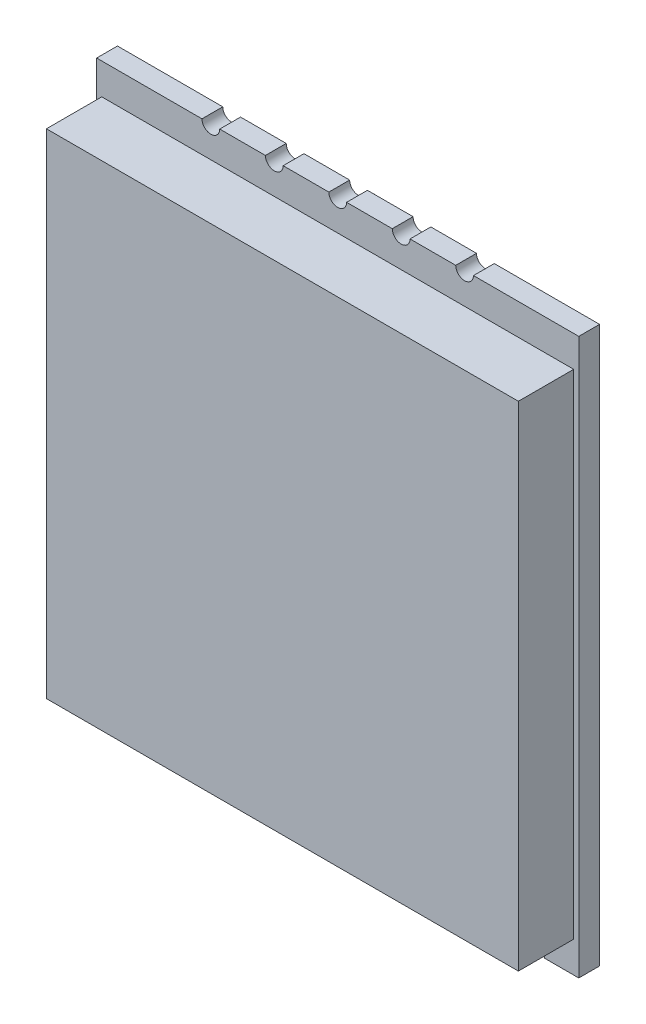
SolidWorks part; units mm, degrees
ref_plane "Front Plane" through (0, 0, 0) normal (0, 0, 1) x (1, 0, 0)
ref_plane "Top Plane" through (0, 0, 0) normal (0, 1, 0) x (1, 0, 0)
ref_plane "Right Plane" through (0, 0, 0) normal (1, 0, 0) x (0, 0, -1)
sketch "Sketch1" plane through (0, 0, 0) normal (0, 0, 1) x (1, 0, 0)
  line L1 (0, 0) -> (19, 0)
  line L2 (0, 0) -> (0, 21.9)
  line L3 (0, 21.9) -> (19, 21.9)
  line L4 (19, 0) -> (19, 21.9)
  dimension "D1" = 19
  dimension "D2" = 21.9
extrude "Boss-Extrude1" add sketch "Sketch1" along normal blind 0.82
sketch "Sketch2" plane through (0, 0, 0.82) normal (0, 0, 1) x (1, 0, 0)
  line L1 (0.2, 1.225) -> (18.8, 1.225)
  line L2 (0.2, 1.225) -> (0.2, 20.675)
  line L3 (0.2, 20.675) -> (18.8, 20.675)
  line L4 (18.8, 1.225) -> (18.8, 20.675)
  line L5 (0, 10.95) -> (0.2, 10.95) construction
  line L6 (0, 21.9) -> (0, 0) construction
  line L7 (18.8, 10.95) -> (19, 10.95) construction
  line L8 (19, 0) -> (19, 21.9) construction
  dimension "D1" = 18.6
  dimension "D2" = 19.45
extrude "Boss-Extrude2" add sketch "Sketch2" along normal blind 2.18
sketch "Sketch3" plane through (0, 0, 0.82) normal (0, 0, 1) x (1, 0, 0)
  line L0 (19, 21.9) -> (0, 21.9) construction
  line L1 (0, 0) -> (19, 0) construction
  line L2 (19, 0) -> (19, 21.9) construction
  circle A0 centre (4.5, 21.9) radius 0.35
  circle A1 centre (7, 21.9) radius 0.35
  circle A2 centre (9.5, 21.9) radius 0.35
  circle A3 centre (12, 21.9) radius 0.35
  circle A4 centre (14.5, 21.9) radius 0.35
  circle A5 centre (4.3, 0) radius 0.35
  circle A6 centre (6.9, 0) radius 0.35
  circle A7 centre (9.5, 0) radius 0.35
  circle A8 centre (12.1, 0) radius 0.35
  circle A9 centre (14.7, 0) radius 0.35
  circle A10 centre (17.3, 0) radius 0.35
  dimension "D1" = 0.7
  dimension "D2" = 4.5
  dimension "D3" = 2.5
  dimension "D4" = 2.5
  dimension "D5" = 2.5
  dimension "D6" = 2.5
  dimension "D7" = 4.5
  dimension "D8" = 1.7
  dimension "D9" = 2.6
  dimension "D10" = 2.6
  dimension "D11" = 2.6
  dimension "D12" = 2.6
  dimension "D13" = 2.6
  dimension "D14" = 4.3
extrude "Cut-Extrude1" cut sketch "Sketch3" against normal through all
